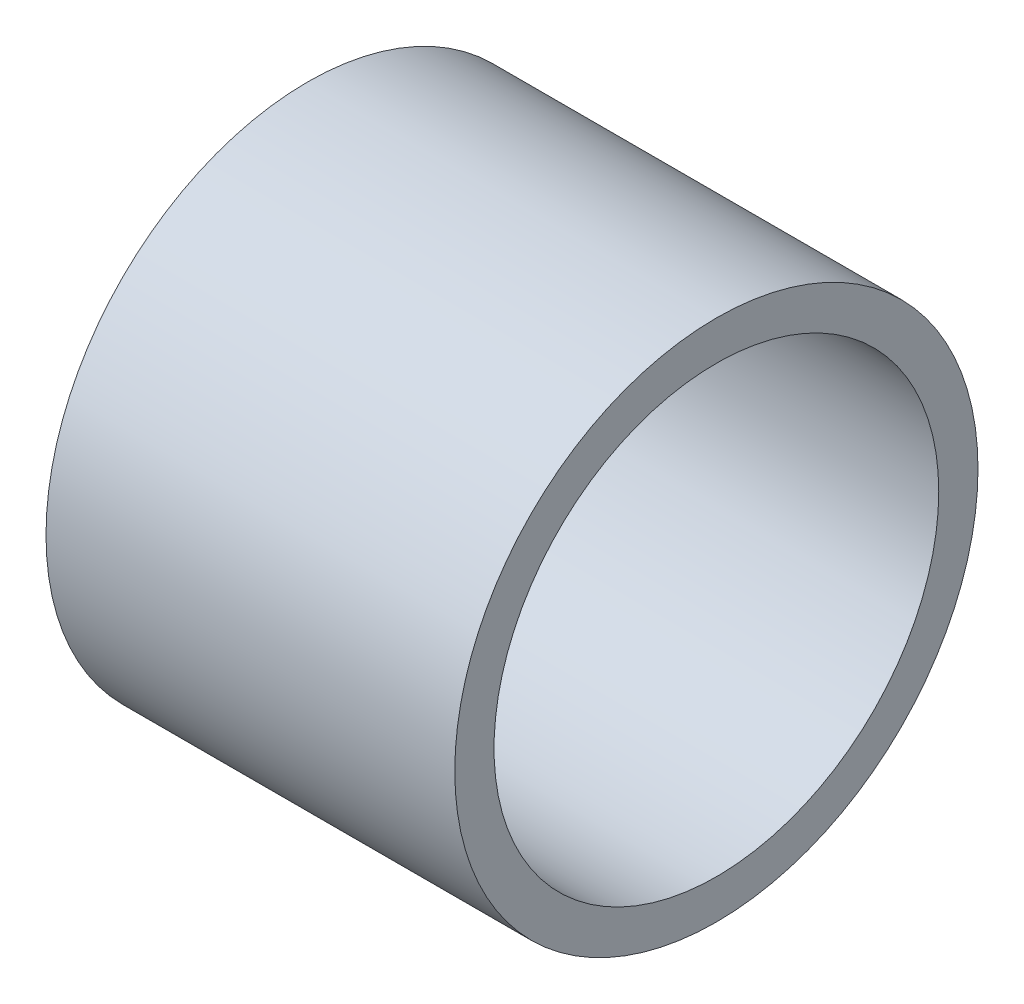
SolidWorks part; units mm, degrees
material "SBR"
ref_plane "Front Plane" through (0, 0, 0) normal (0, 0, 1) x (1, 0, 0)
ref_plane "Top Plane" through (0, 0, 0) normal (0, 1, 0) x (1, 0, 0)
ref_plane "Right Plane" through (0, 0, 0) normal (1, 0, 0) x (0, 0, -1)
sketch "Sketch1" plane through (0, 0, 0) normal (1, 0, 0) x (0, 0, -1)
  circle A0 centre (0, 0) radius 16
  circle A1 centre (0, 0) radius 13.6
  dimension "D1" = 32
  dimension "D2" = 27.2
extrude "Boss-Extrude1" add sketch "Sketch1" along normal blind 25
